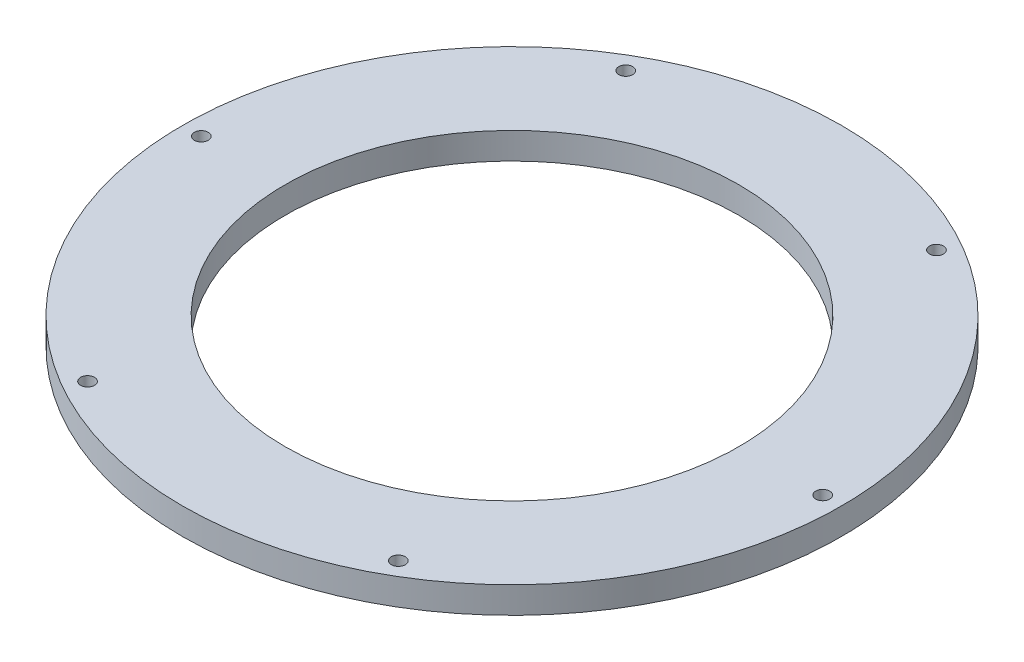
SolidWorks part; units mm, degrees
material "Pine"
ref_plane "Front Plane" through (0, 0, 0) normal (0, 0, 1) x (1, 0, 0)
ref_plane "Top Plane" through (0, 0, 0) normal (0, 1, 0) x (1, 0, 0)
ref_plane "Right Plane" through (0, 0, 0) normal (1, 0, 0) x (0, 0, -1)
sketch "Sketch1" plane through (0, 0, 0) normal (0, 1, 0) x (1, 0, 0)
  circle A0 centre (0, 0) radius 236
  circle A1 centre (0, 0) radius 162.5
  dimension "D1" = 472
  dimension "D2" = 325
extrude "Boss-Extrude1" add sketch "Sketch1" along normal mid plane 19
sketch "Sketch2" plane through (0, 9.5, 0) normal (0, 1, 0) x (1, 0, 0)
  line L0 (0, -1000) -> (0, 49000) construction
  line L1 (-1000, 0) -> (49000, 0) construction
  line L2 (-500, -866.0254) -> (24500, 42435.2448) construction
  line L3 (-500, 866.0254) -> (24500, -42435.2448) construction
  circle A0 centre (-111.25, 192.6907) radius 5
  circle A1 centre (222.5, 0) radius 5
  circle A2 centre (111.25, 192.6907) radius 5
  circle A3 centre (-222.5, 0) radius 5
  circle A4 centre (111.25, -192.6907) radius 5
  circle A5 centre (-111.25, -192.6907) radius 5
  point P16 (-222.5, 0)
  dimension "D1" = 10
  dimension "D2" = 10
  dimension "D3" = 222.5
  dimension "D4" = 222.5
extrude "Cut-Extrude1" cut sketch "Sketch2" against normal through all
